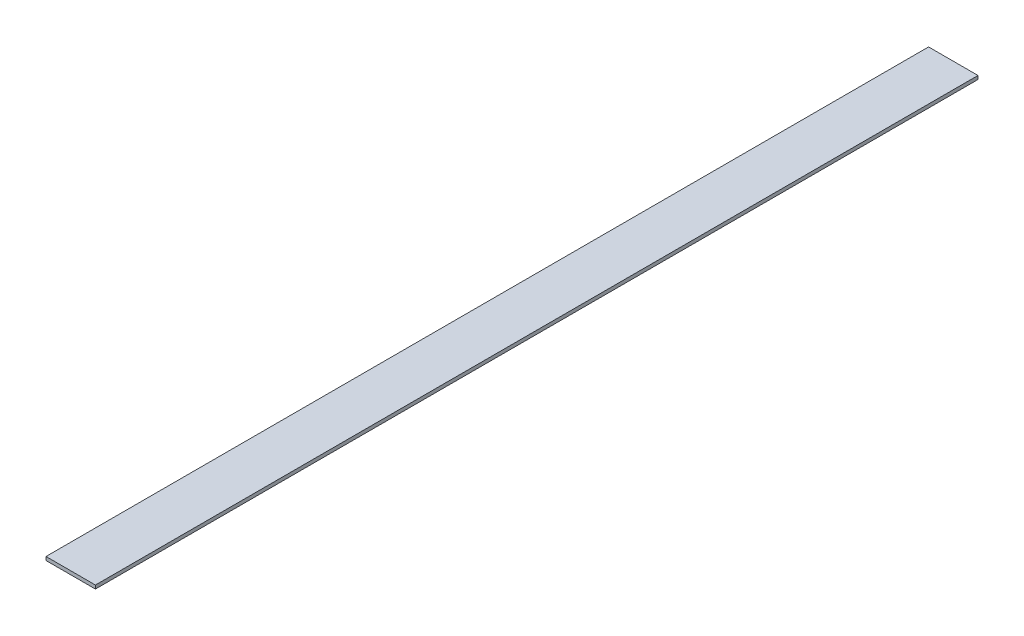
SolidWorks part; units mm, degrees
ref_plane "Front Plane" through (0, 0, 0) normal (0, 0, 1) x (1, 0, 0)
ref_plane "Top Plane" through (0, 0, 0) normal (0, 1, 0) x (1, 0, 0)
ref_plane "Right Plane" through (0, 0, 0) normal (1, 0, 0) x (0, 0, -1)
sketch "Sketch1" plane through (0, 0, 0) normal (0, 0, 1) x (1, 0, 0)
  line L1 (0, 0) -> (140, 0)
  line L2 (0, 0) -> (0, -10)
  line L3 (0, -10) -> (140, -10)
  line L4 (140, 0) -> (140, -10)
  dimension "D1" = 10
  dimension "D2" = 140
extrude "Boss-Extrude1" add sketch "Sketch1" along normal blind 2500
